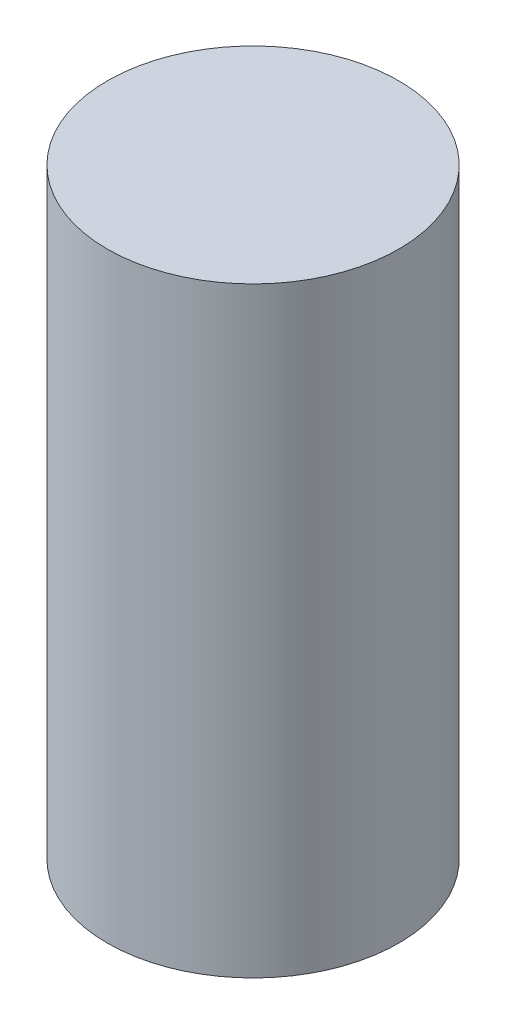
SolidWorks part; units mm, degrees
ref_plane "前视基准面" through (0, 0, 0) normal (0, 0, 1) x (1, 0, 0)
ref_plane "上视基准面" through (0, 0, 0) normal (0, 1, 0) x (1, 0, 0)
ref_plane "右视基准面" through (0, 0, 0) normal (1, 0, 0) x (0, 0, -1)
other "Configuration Table"
sketch "草图1" plane through (0, 0, 0) normal (0, 1, 0) x (1, 0, 0)
  circle A0 centre (0, 0) radius 4.85
  dimension "D1" = 9.7
extrude "凸台-拉伸1" add sketch "草图1" along normal blind 20
